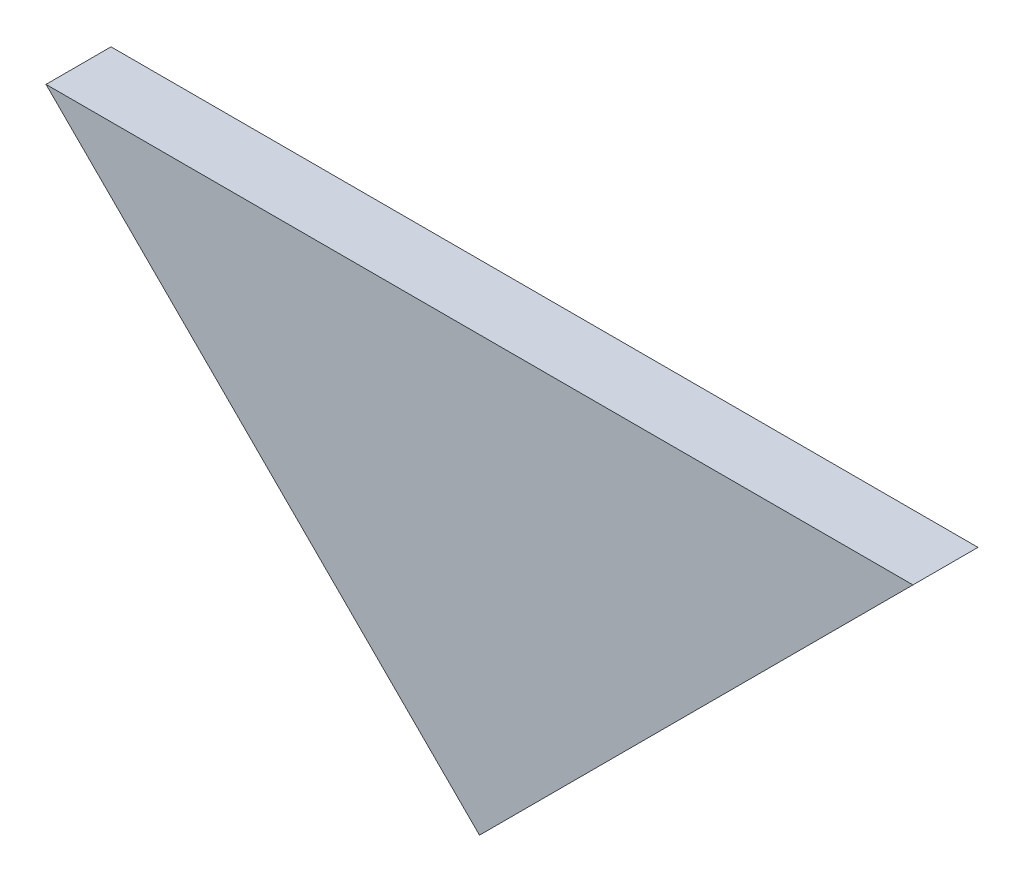
SolidWorks part; units mm, degrees
ref_plane "Front Plane" through (0, 0, 0) normal (0, 0, 1) x (1, 0, 0)
ref_plane "Top Plane" through (0, 0, 0) normal (0, 1, 0) x (1, 0, 0)
ref_plane "Right Plane" through (0, 0, 0) normal (1, 0, 0) x (0, 0, -1)
sketch "Sketch1" plane through (0, 0, 0) normal (0, 0, 1) x (1, 0, 0)
  line L0 (0, 0) -> (40, 40)
  line L1 (40, 40) -> (-40, 40)
  line L2 (-40, 40) -> (0, 0)
  line L3 (0, 0) -> (0, 40) construction
  dimension "D1" = 40
  dimension "D2" = 90
extrude "Boss-Extrude1" add sketch "Sketch1" along normal blind 6 contours L1 L2 L0
